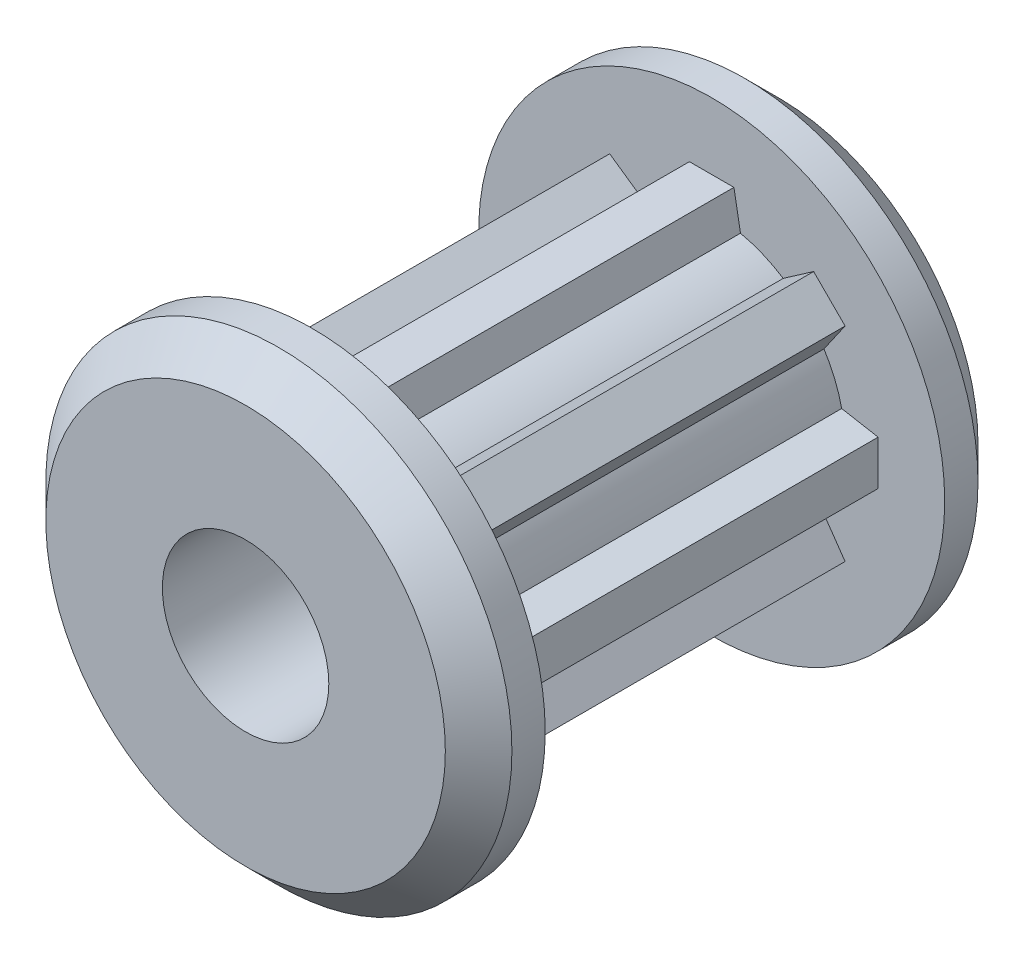
SolidWorks part; units mm, degrees
ref_plane "Front (XY)" through (0, 0, 0) normal (0, 0, 1) x (1, 0, 0)
ref_plane "Top (XZ)" through (0, 0, 0) normal (0, 1, 0) x (1, 0, 0)
ref_plane "Right (YZ)" through (0, 0, 0) normal (1, 0, 0) x (0, 0, -1)
sketch "Sketch1" plane through (0, 0, 0) normal (0, 0, 1) x (1, 0, 0)
  circle A0 centre (0, 0) radius 4
  dimension "D1" = 8
extrude "Boss-Extrude1" add sketch "Sketch1" along normal mid plane 12
sketch "Sketch2" plane through (0, 0, 6) normal (0, 0, 1) x (1, 0, 0)
  circle A2 centre (0, 0) radius 7
  circle A3 centre (0, 0) radius 7
  dimension "D1" = 3
extrude "Boss-Extrude2" add sketch "Sketch2" along normal blind 2
pattern_linear "LPattern1" count 2 spacing 14 along (0, 0, -1) of "Boss-Extrude2"
sketch "Sketch3" plane through (0, 0, 0) normal (0, 0, 1) x (1, 0, 0)
  circle A0 centre (0, 0) radius 2.5
  dimension "D1" = 5
extrude "Cut-Extrude1" cut sketch "Sketch3" against normal through all both and the other way through all
chamfer "Chamfer1" distance 1 angle 45 2 edges at (7, 0, -8) (7, 0, 8)
sketch "Sketch6" plane through (0, 0, 0) normal (0, 0, 1) x (1, 0, 0)
  line L0 (1.1, 2.6) -> (0.6682, 5)
  line L1 (0.6682, 5) -> (-0.6682, 5)
  line L2 (-0.6682, 5) -> (-1.1, 2.6)
  line L3 (-1.1, 2.6) -> (1.1, 2.6)
  point P2 (0, 5)
  point P5 (0, 2.6)
  dimension "D1" = 2.4
  dimension "D2" = 1.3364
  dimension "D3" = 2.6
  dimension "D4" = 2.2
extrude "Boss-Extrude3" add sketch "Sketch6" along normal mid plane 12
sketch "Sketch7" plane through (0, 0, 0) normal (0, 1, 0) x (1, 0, 0)
  line L0 (0, 0) -> (0, 3) construction
  dimension "D1" = 3
pattern_circular "CirPattern1" count 8 over 360 about axis through (0, 0, 0) along (0, 0, 1) of "Boss-Extrude3"
